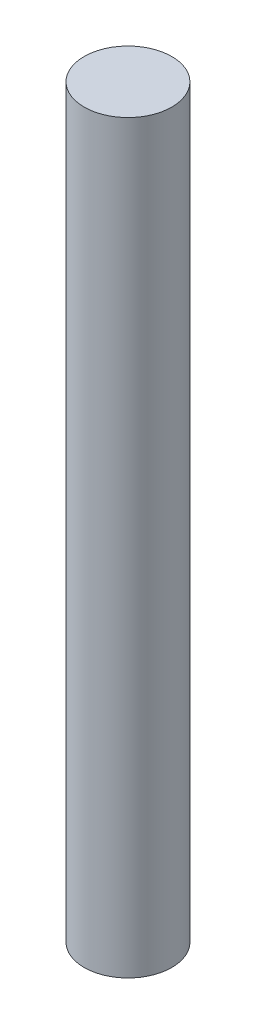
SolidWorks part; units mm, degrees
ref_plane "Alzado" through (0, 0, 0) normal (0, 0, 1) x (1, 0, 0)
ref_plane "Planta" through (0, 0, 0) normal (0, 1, 0) x (1, 0, 0)
ref_plane "Vista lateral" through (0, 0, 0) normal (1, 0, 0) x (0, 0, -1)
sketch "Croquis1" plane through (0, 0, 0) normal (0, 1, 0) x (1, 0, 0)
  circle A0 centre (0, 0) radius 5
  dimension "D1" = 10
extrude "Saliente-Extruir1" add sketch "Croquis1" along normal blind 85
